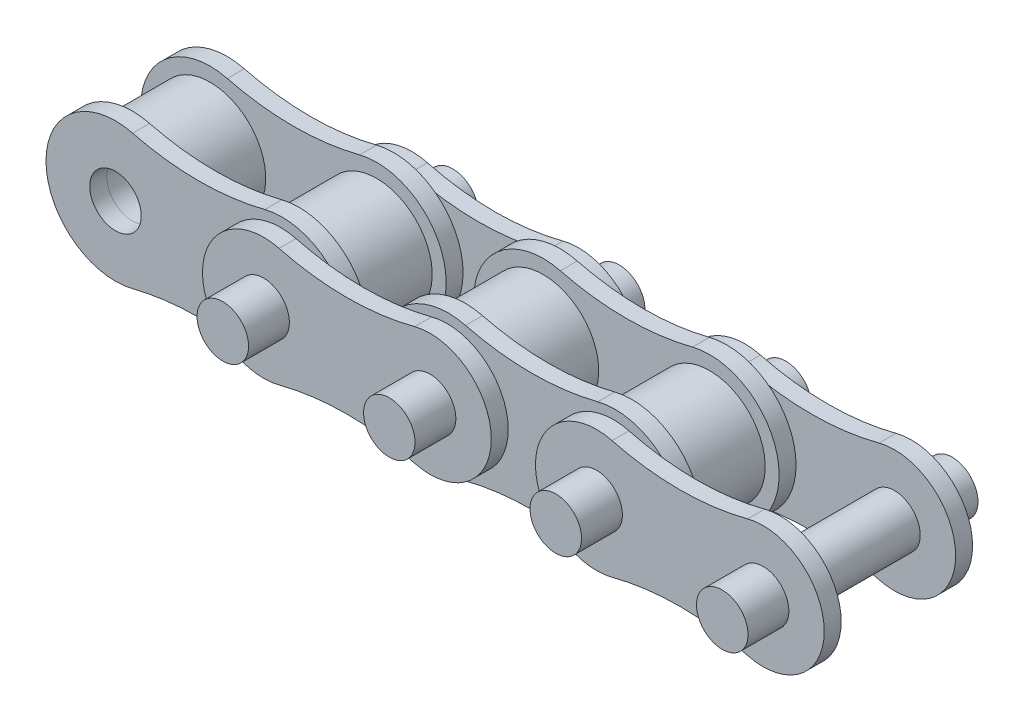
SolidWorks part; units mm, degrees
ref_plane "Front Plane" through (0, 0, 0) normal (0, 0, 1) x (1, 0, 0)
ref_plane "Top Plane" through (0, 0, 0) normal (0, 1, 0) x (1, 0, 0)
ref_plane "Right Plane" through (0, 0, 0) normal (1, 0, 0) x (0, 0, -1)
sketch "Sketch1" plane through (0, 0, 0) normal (0, 0, 1) x (1, 0, 0)
  line L0 (-2.9972, 0) -> (2.9972, 0) construction
  line L1 (-2.9972, 2.5019) -> (-2.9972, -2.5019) construction
  line L2 (0, -2.1266) -> (0, 2.1266) construction
  circle A0 centre (-2.9972, 0) radius 2
  circle A1 centre (2.9972, 0) radius 2
  circle A2 centre (-2.9972, 0) radius 0.9271
  circle A3 centre (2.9972, 0) radius 0.9271
  arc A4 (-2.3803, 2.4247) -> (-2.3803, -2.4247) centre (-2.9972, 0) ccw
  arc A5 (2.3803, -2.4247) -> (2.3803, 2.4247) centre (2.9972, 0) ccw
  arc A6 (-2.3803, 2.4247) -> (2.3803, 2.4247) centre (0, 11.7809) ccw
  arc A7 (-2.3803, -2.4247) -> (2.3803, -2.4247) centre (0, -11.7809) cw
  dimension "Roller Dia" = 4
  dimension "Pin Dia" = 1.8542
  dimension "Pitch" = 5.9944
  dimension "H" = 5.0038
  dimension "D2" = 4.2532
sketch "Sketch2" plane through (0, 0, 0) normal (0, 1, 0) x (1, 0, 0)
  line L0 (0, 1.4) -> (0, -1.4) construction
  point P2 (0, -2.0096)
  point P4 (0, 2.0096)
  point P5 (0, 2.0604)
  point P6 (0, 2.67)
  dimension "W" = 2.8
  dimension "T" = 0.6096
  dimension "D1" = 0.6096
  dimension "T1" = 0.6096
  dimension "D3" = 0.0508
ref_plane "Plane1" through (0, 0, 1.4) normal (0, 0, 1) x (1, 0, 0)
ref_plane "Plane2" through (0, 0, -2.0604) normal (0, 0, 1) x (1, 0, 0)
sketch "Sketch4" plane through (0, 0, 0) normal (0, 0, 1) x (1, 0, 0)
  circle A0 centre (-2.9972, 0) radius 2 construction
  circle A1 centre (-2.9972, 0) radius 2
  circle A2 centre (2.9972, 0) radius 2 construction
  circle A3 centre (2.9972, 0) radius 2
  circle A4 centre (-2.9972, 0) radius 0.9525
  circle A5 centre (2.9972, 0) radius 0.9525
  dimension "D1" = 1.905
  dimension "D2" = 1.905
extrude "Boss-Extrude1" add sketch "Sketch4" along normal mid plane 2.8
sketch "Sketch5" plane through (0, 0, 1.4) normal (0, 0, 1) x (1, 0, 0)
  arc A0 (-2.3803, 2.4247) -> (-2.3803, -2.4247) centre (-2.9972, 0) ccw construction
  arc A1 (-2.3803, 2.4247) -> (2.3803, 2.4247) centre (0, 11.7809) ccw construction
  circle A2 centre (-2.9972, 0) radius 0.9271 construction
  arc A3 (2.3803, -2.4247) -> (2.3803, 2.4247) centre (2.9972, 0) ccw construction
  circle A4 centre (2.9972, 0) radius 0.9271 construction
  arc A5 (2.3803, -2.4247) -> (-2.3803, -2.4247) centre (0, -11.7809) ccw construction
  arc A6 (-2.3803, 2.4247) -> (-2.3803, -2.4247) centre (-2.9972, 0) ccw
  arc A7 (-2.3803, 2.4247) -> (2.3803, 2.4247) centre (0, 11.7809) ccw
  circle A8 centre (-2.9972, 0) radius 0.9271
  arc A9 (2.3803, -2.4247) -> (2.3803, 2.4247) centre (2.9972, 0) ccw
  circle A10 centre (2.9972, 0) radius 0.9271
  arc A11 (2.3803, -2.4247) -> (-2.3803, -2.4247) centre (0, -11.7809) ccw
extrude "Boss-Extrude2" add sketch "Sketch5" along normal up to vertex (0.6096 mm away) separate body up to point (0, 0, 2.0096)
pattern_linear "LPattern1" count 2 spacing 5.9944 along (1, 0, 0) of bodies 102
sketch "Sketch7" plane through (0, 0, -2.0604) normal (0, 0, 1) x (1, 0, 0)
  line L0 (8.9916, 2.2017) -> (8.9916, -2.2017) construction
  arc A0 (3.5538, 2.1302) -> (3.5538, -2.1302) centre (2.9972, 0) ccw
  arc A1 (8.435, -2.1302) -> (8.435, 2.1302) centre (8.9916, 0) ccw
  arc A2 (2.3803, -2.4247) -> (2.3803, 2.4247) centre (2.9972, 0) ccw construction
  circle A3 centre (8.9916, 0) radius 2 construction
  arc A4 (3.5538, 2.1302) -> (8.435, 2.1302) centre (5.9944, 11.4708) ccw
  arc A5 (3.5538, -2.1302) -> (8.435, -2.1302) centre (5.9944, -11.4708) cw
  arc A6 (-2.3803, 2.4247) -> (2.3803, 2.4247) centre (0, 11.7809) ccw construction
  circle A7 centre (2.9972, 0) radius 0.9271 construction
  circle A8 centre (2.9972, 0) radius 0.9271
  circle A9 centre (8.9916, 0) radius 0.9271
  dimension "D2" = 4.4033
extrude "Boss-Extrude3" add sketch "Sketch7" against normal up to vertex (0.6096 mm away) separate body up to point (0, 0, -2.67)
mirror "Mirror1" about plane through (0, 0, 0) normal (0, 0, 1) of bodies 103 105
sketch "Sketch8" plane through (0, 0, 0) normal (0, 0, 1) x (1, 0, 0)
  circle A0 centre (2.9972, 0) radius 0.9271
  circle A1 centre (8.9916, 0) radius 0.9271
  circle A2 centre (2.9972, 0) radius 0.9271 construction
  circle A3 centre (8.9916, 0) radius 0.9271 construction
extrude "Boss-Extrude4" add sketch "Sketch8" against normal blind 4.1402 and the other way blind 4.1402 separate body
pattern_linear "LPattern2" count 2 spacing 11.9888 along (1, 0, 0) of bodies 109 108 107 106 105 104 103 102 101
delete or keep bodies "Body-Delete1" type delete bodies bodies 115
combine bodies "Combine1" operation type add bodies to combine 102 103 104 105 106 107 108 109 110 111 112 113 114 116 117 118 101
sketch "Sketch9" plane through (0, 0, 0) normal (0, 0, 1) x (1, 0, 0)
  line L0 (20.9804, 2.2017) -> (20.9804, -2.2017) construction
  line L1 (14.986, 2.5019) -> (14.986, -2.5019) construction
  arc A0 (14.3691, -2.4247) -> (14.3691, 2.4247) centre (14.986, 0) ccw construction
  arc A1 (14.986, -2.5019) -> (14.986, 2.5019) centre (14.986, 0) ccw
  arc A2 (20.4238, -2.1302) -> (20.4238, 2.1302) centre (20.9804, 0) ccw construction
  arc A3 (20.9804, -2.2017) -> (20.9804, 2.2017) centre (20.9804, 0) ccw
  circle A4 centre (-2.9972, 0) radius 2 construction
  circle A5 centre (-2.9972, 0) radius 2
equation "\"D2@Sketch1\" =\"H@Sketch1\"*.85"
equation "\"D1@Sketch2\" = \"T@Sketch2\""
equation "\"D1@Sketch4\" = \"Pin Dia@Sketch1\"+.002"
equation "\"D2@Sketch4\" = \"D1@Sketch4\""
equation "\"D1@Boss-Extrude1\" = \"W@Sketch2\""
equation "\"D3@LPattern1\" = \"Pitch@Sketch1\""
equation "\"D3@LPattern2\" = \"Pitch@Sketch1\"*2"
equation "\"D2@Sketch7\" = \"H@Sketch1\"*.88"
